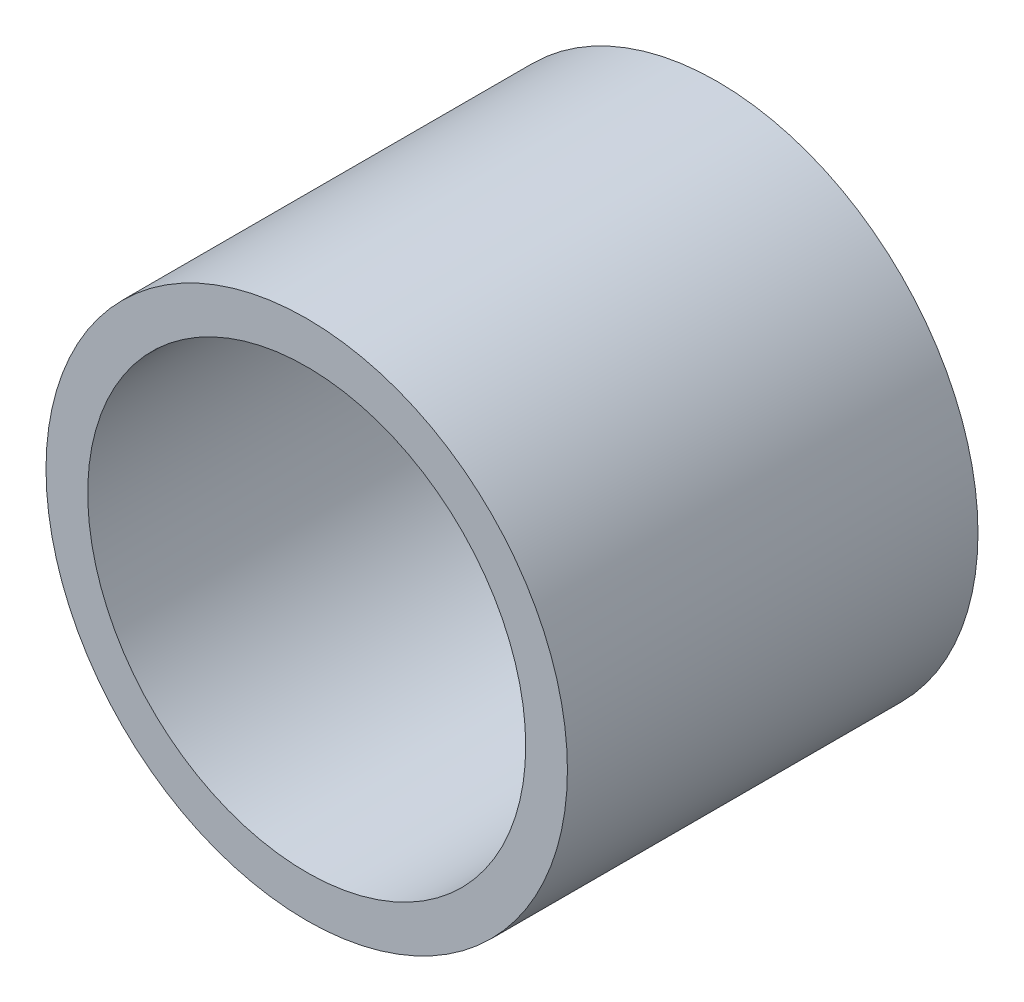
SolidWorks part; units mm, degrees
material "6061-T6 (SS)"
ref_plane "Front Plane" through (0, 0, 0) normal (0, 0, 1) x (1, 0, 0)
ref_plane "Top Plane" through (0, 0, 0) normal (0, 1, 0) x (1, 0, 0)
ref_plane "Right Plane" through (0, 0, 0) normal (1, 0, 0) x (0, 0, -1)
sketch "Sketch1" plane through (0, 0, 0) normal (0, 0, 1) x (1, 0, 0)
  circle A0 centre (0, 0) radius 3.175
  circle A1 centre (0, 0) radius 2.667
  dimension "D1" = 6.35
  dimension "D2" = 0.508
extrude "Boss-Extrude1" add sketch "Sketch1" along normal blind 5
